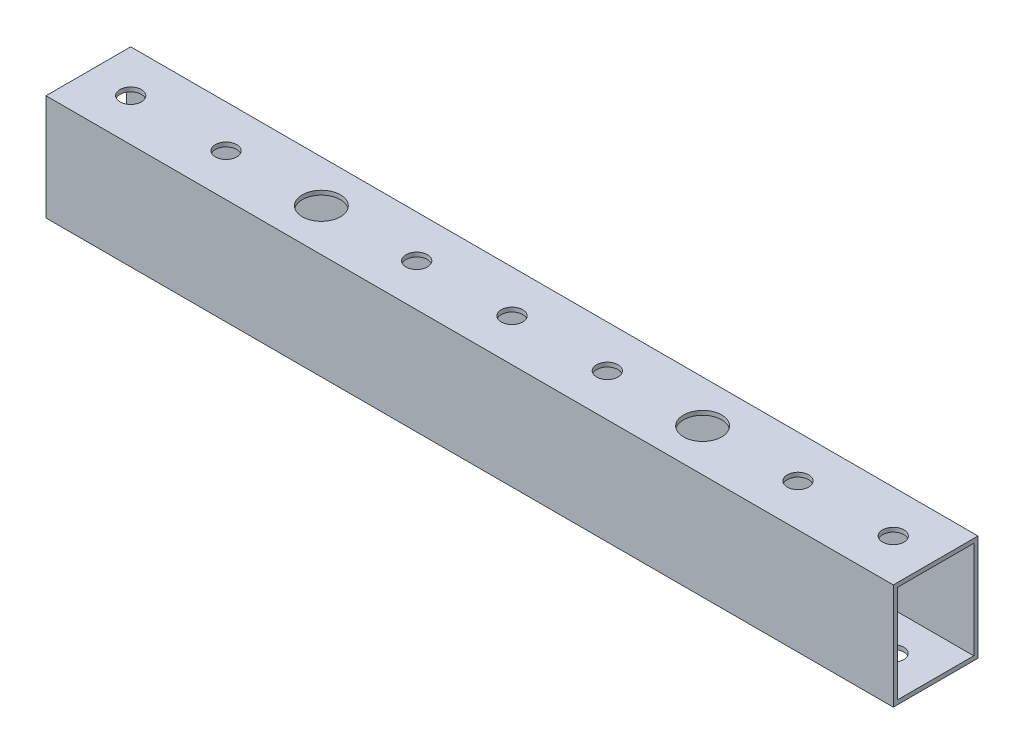
SolidWorks part; units mm, degrees
material "1060 合金"
ref_plane "前视基准面" through (0, 0, 0) normal (0, 0, 1) x (1, 0, 0)
ref_plane "上视基准面" through (0, 0, 0) normal (0, 1, 0) x (1, 0, 0)
ref_plane "右视基准面" through (0, 0, 0) normal (1, 0, 0) x (0, 0, -1)
other "Configuration Table"
sketch "草图1" plane through (0, 0, 0) normal (1, 0, 0) x (0, 0, -1)
  line L0 (-10, -12.5) -> (-10, 12.5)
  line L1 (-9, -11.5) -> (9, -11.5)
  line L2 (-9, -11.5) -> (-9, 11.5)
  line L3 (-9, 11.5) -> (9, 11.5)
  line L4 (9, -11.5) -> (9, 11.5)
  line L5 (-9, -11.5) -> (9, 11.5) construction
  line L6 (-9, 11.5) -> (9, -11.5) construction
  line L7 (-10, 12.5) -> (10, 12.5)
  line L8 (10, -12.5) -> (10, 12.5)
  line L9 (-10, -12.5) -> (10, -12.5)
  point P0 (0, 0)
  dimension "D1" = 1
  dimension "D2" = 20
  dimension "D3" = 25
extrude "凸台-拉伸1" add sketch "草图1" along normal mid plane 200
sketch "草图2" plane through (0, 12.5, 0) normal (0, 1, 0) x (1, 0, 0)
  line L0 (-100, 0) -> (100, 0) construction
  line L1 (-100, 10) -> (-100, -10) construction
  line L2 (100, 10) -> (100, -10) construction
  circle A0 centre (0, 0) radius 2.525
  circle A1 centre (-90, 0) radius 2.525
  circle A2 centre (90, 0) radius 2.525
  dimension "D1" = 5.05
  dimension "D2" = 90
  dimension "D3" = 90
extrude "切除-拉伸1" cut sketch "草图2" against normal mid plane 10
sketch "草图4" plane through (0, -11.5, 0) normal (0, 1, 0) x (1, 0, 0)
  circle A0 centre (-90, 0) radius 2.5
  circle A1 centre (0, 0) radius 2.5
  circle A2 centre (90, 0) radius 2.5
  dimension "D1" = 5
extrude "切除-拉伸3" cut sketch "草图4" against normal mid plane 10
sketch "草图5" plane through (0, 12.5, 0) normal (0, 1, 0) x (1, 0, 0)
  line L0 (-45, 0) -> (45, 0) construction
  line L1 (-90, 0) -> (0, 0) construction
  circle A0 centre (-45, 0) radius 4.5
  circle A1 centre (45, 0) radius 4.5
  point P5 (0, 0)
  dimension "D1" = 9
extrude "切除-拉伸4" cut sketch "草图5" against normal blind 2
sketch "草图6" plane through (0, -11.5, 0) normal (0, 1, 0) x (1, 0, 0)
  circle A0 centre (-45, 0) radius 2.525
  circle A1 centre (45, 0) radius 2.525
  dimension "D1" = 5.05
extrude "切除-拉伸5" cut sketch "草图6" against normal blind 2
sketch "草图7" plane through (0, 12.5, 0) normal (0, 1, 0) x (1, 0, 0)
  line L0 (-90, 0) -> (-45, 0) construction
  line L1 (-45, 0) -> (0, 0) construction
  line L2 (0, 0) -> (45, 0) construction
  line L3 (45, 0) -> (90, 0) construction
  circle A0 centre (-67.5, 0) radius 2.525
  circle A1 centre (-22.5, 0) radius 2.525
  circle A2 centre (22.5, 0) radius 2.525
  circle A3 centre (67.5, 0) radius 2.525
  circle A4 centre (-90, 0) radius 2.525 construction
extrude "切除-拉伸6" cut sketch "草图7" against normal blind 10
